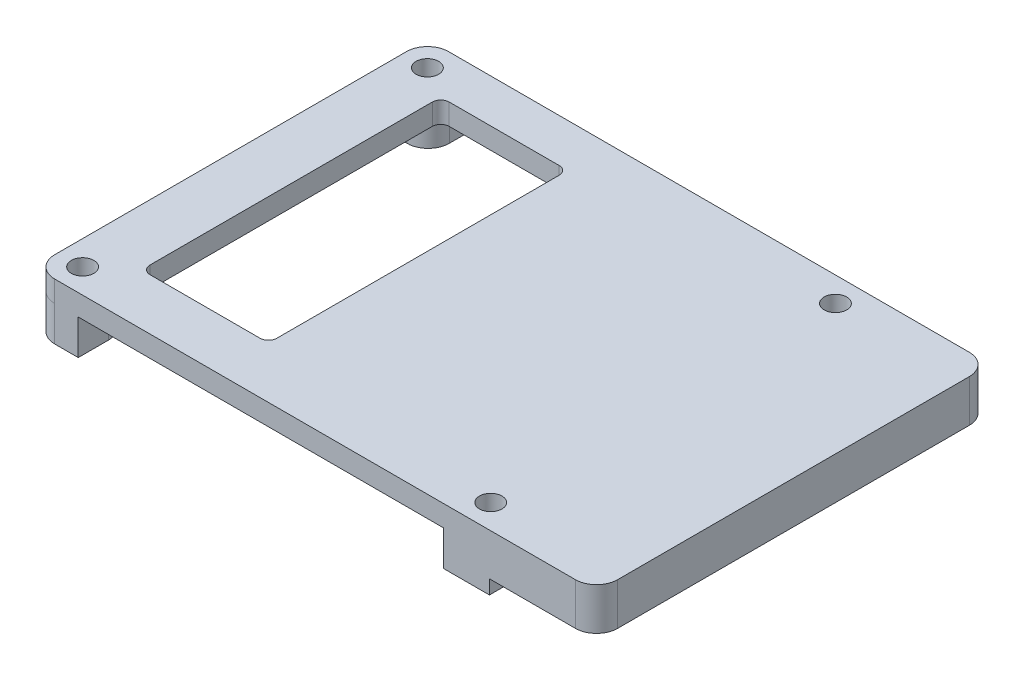
SolidWorks part; units mm, degrees
material "7075-T6 (SN)"
ref_plane "前视基准面" through (0, 0, 0) normal (0, 0, 1) x (1, 0, 0)
ref_plane "上视基准面" through (0, 0, 0) normal (0, 1, 0) x (1, 0, 0)
ref_plane "右视基准面" through (0, 0, 0) normal (1, 0, 0) x (0, 0, -1)
other "Configuration Table"
sketch "草图1" plane through (0, 0, 0) normal (0, 1, 0) x (1, 0, 0)
  line L0 (-70.9525, 18.3001) -> (-70.9986, 18.1669) construction
  line L5 (-80.009, 21.4027) -> (-0.009, 21.4027) construction
  line L6 (-0.009, 21.39) -> (-0.009, -28.5917)
  line L7 (-53.9406, -24.2884) -> (-53.9406, -23.4455) construction
  line L12 (-80.009, 21.4027) -> (-80.009, -28.6044)
  line L13 (-77.0217, -31.5917) -> (12.7873, -31.5917)
  line L14 (15.7746, -28.6044) -> (15.7746, 21.4027)
  line L15 (12.7873, 24.39) -> (-77.0217, 24.39)
  line L16 (-80.009, 21.4027) -> (-80.009, -28.6044)
  line L17 (-77.0217, -31.5917) -> (-3.009, -31.5917)
  line L19 (-3.009, 24.39) -> (-77.0217, 24.39)
  line L20 (-57.0741, 18.2303) -> (-57.0142, 16.884) construction
  line L21 (-57.0142, 16.884) -> (-53.9406, 15.8369) construction
  line L24 (-71.9124, -31.5917) -> (-71.9124, -38.4632) construction
  line L26 (-55.8106, -26.0508) -> (-55.3191, -21.9005) construction
  line L27 (-55.3191, -21.9005) -> (-52.2337, -21.9005) construction
  line L28 (-57.0741, 18.2303) -> (-53.9406, 18.2303) construction
  line L30 (-53.9406, 15.8369) -> (-53.9406, 18.2303) construction
  line L31 (-71.9686, 17.09) -> (-71.9659, 15.0188) construction
  line L32 (-54.4169, -24.2884) -> (-53.9406, -24.2884) construction
  line L33 (-70.9986, 18.1669) -> (-70.8339, 18.1567) construction
  line L34 (-70.8339, 18.1567) -> (-70.8158, 18.2696) construction
  line L35 (-70.8158, 18.2696) -> (-70.9525, 18.3001) construction
  line L36 (-70.8221, 18.2303) -> (-69.2002, 18.2303) construction
  line L38 (-70.7701, 18.2303) -> (-55.1406, 18.2303)
  line L39 (-71.9701, 17.0303) -> (-71.9701, -23.0884)
  line L40 (-70.7701, -24.2884) -> (-55.1406, -24.2884)
  line L41 (-53.9406, 17.0303) -> (-53.9406, -23.0884)
  arc A0 (-70.7701, 18.2303) -> (-71.9701, 17.0303) centre (-70.7701, 17.0303) ccw
  arc A1 (-53.9406, 17.0303) -> (-55.1406, 18.2303) centre (-55.1406, 17.0303) ccw
  arc A2 (-53.9406, -23.0884) -> (-55.1406, -24.2884) centre (-55.1406, -23.0884) cw
  arc A3 (-70.7701, -24.2884) -> (-71.9701, -23.0884) centre (-70.7701, -23.0884) cw
  circle A4 centre (-76.5285, 20.8867) radius 1.6
  circle A5 centre (-18.5286, 20.8866) radius 1.6
  circle A6 centre (-18.5283, -28.1137) radius 1.6
  circle A7 centre (-76.5283, -28.1135) radius 1.6
  arc A8 (-80.009, -28.6044) -> (-77.0217, -31.5917) centre (-77.0217, -28.6044) ccw
  arc A9 (12.7873, -31.5917) -> (15.7746, -28.6044) centre (12.7873, -28.6044) ccw
  arc A10 (15.7746, 21.4027) -> (12.7873, 24.39) centre (12.7873, 21.4027) ccw
  arc A11 (-77.0217, 24.39) -> (-80.009, 21.4027) centre (-77.0217, 21.4027) ccw
  arc A12 (-80.009, -28.6044) -> (-77.0217, -31.5917) centre (-77.0217, -28.6044) ccw
  arc A15 (-77.0217, 24.39) -> (-80.009, 21.4027) centre (-77.0217, 21.4027) ccw
  arc A19 (-0.009, 21.39) -> (-3.009, 24.39) centre (-3.009, 21.39) ccw
  arc A20 (-0.009, -28.5917) -> (-3.009, -31.5917) centre (-3.009, -28.5917) cw
  dimension "D2" = 3.2
  dimension "D3" = 3.2
  dimension "D4" = 3.2
  dimension "D5" = 3.2
  dimension "D6" = 3
  dimension "D7" = 1.2
  dimension "D8" = 1.2
  dimension "D9" = 1.2
  dimension "D10" = 1.2
  dimension "D11" = 3
  dimension "D1" = 0
extrude "凸台-拉伸1" add sketch "草图1" along normal blind 3
sketch "草图3" plane through (0, 0, 0) normal (0, -1, 0) x (1, 0, 0)
  line L0 (-77.0217, 31.5917) -> (-3.009, 31.5917) construction
  line L1 (-15.2271, 31.5917) -> (-3.009, 31.5917)
  line L2 (-15.2271, 31.5917) -> (-15.2271, -24.39)
  line L3 (-15.2271, -24.39) -> (-3.009, -24.39)
  line L7 (-36.8658, -15.5141) -> (-24.8441, -15.5141)
  line L8 (-36.8658, -15.5141) -> (-36.8658, 23.3522)
  line L9 (-36.8658, 23.3522) -> (-24.8441, 23.3522)
  line L10 (-24.8441, -15.5141) -> (-24.8441, 23.3522)
  line L11 (-0.009, 28.5917) -> (-0.009, -21.39)
  arc A0 (-0.009, -21.39) -> (-3.009, -24.39) centre (-3.009, -21.39) cw
  arc A1 (-3.009, 31.5917) -> (-0.009, 28.5917) centre (-3.009, 28.5917) cw
  dimension "D1" = 3
  dimension "D2" = 3
extrude "凸台-拉伸3" add sketch "草图3" along normal blind 3
sketch "草图4" plane through (0, 0, 0) normal (0, -1, 0) x (1, 0, 0)
  line L0 (-80.009, 24.3217) -> (-76.6695, 24.3217)
  line L1 (-80.009, -21.4027) -> (-80.009, 28.6044) construction
  line L2 (-15.2271, 31.5917) -> (-15.2271, -24.39) construction
  line L3 (-15.2271, 24.3217) -> (-15.2271, 31.5917)
  line L4 (-15.2271, 31.5917) -> (-21.7271, 31.5917)
  line L5 (-77.0217, 31.5917) -> (-15.2271, 31.5917) construction
  line L6 (-21.7271, 31.5917) -> (-21.7271, 27.3217)
  line L7 (-21.7271, -21.1423) -> (-21.7271, -24.39)
  line L8 (-73.6695, 27.3217) -> (-73.6695, 31.5917)
  line L9 (-18.7271, 24.3217) -> (-15.2271, 24.3217)
  line L10 (-80.009, 24.3217) -> (-80.009, 28.5917)
  line L11 (-77.009, 31.5917) -> (-73.6695, 31.5917)
  line L16 (-80.009, -18.1423) -> (-76.6695, -18.1423)
  line L17 (-73.6695, -21.1423) -> (-73.6695, -24.3882)
  line L18 (-73.6695, -24.3882) -> (-77.009, -24.3882)
  line L19 (-80.009, -21.3882) -> (-80.009, -18.1423)
  line L20 (-18.7271, -18.1423) -> (-15.2271, -18.1423) construction
  line L21 (-18.7271, -18.1423) -> (-15.2271, -18.1423)
  line L22 (-15.2271, -18.1423) -> (-15.2271, -24.39)
  line L23 (-15.2271, -24.39) -> (-21.7271, -24.39)
  line L24 (-15.2271, -24.39) -> (-77.0217, -24.39) construction
  line L25 (-73.6695, -19.7285) -> (-73.6695, -28.5591) construction
  line L34 (-76.6695, -18.1423) -> (-92.8145, -18.1423) construction
  circle A0 centre (-76.5283, 28.1135) radius 1.6
  circle A1 centre (-18.5283, 28.1137) radius 1.6
  circle A2 centre (-18.5286, -20.8866) radius 1.6
  circle A3 centre (-76.5285, -20.8867) radius 1.6
  arc A4 (-80.009, 28.5917) -> (-77.009, 31.5917) centre (-77.009, 28.5917) cw
  arc A6 (-77.009, -24.3882) -> (-80.009, -21.3882) centre (-77.009, -21.3882) cw
  arc A10 (-18.7271, 24.3217) -> (-21.7271, 27.3217) centre (-18.7271, 27.3217) cw
  arc A11 (-18.7271, -18.1423) -> (-21.7271, -21.1423) centre (-18.7271, -21.1423) ccw
  arc A12 (-73.6695, -21.1423) -> (-76.6695, -18.1423) centre (-76.6695, -21.1423) ccw
  arc A13 (-73.6695, 27.3217) -> (-76.6695, 24.3217) centre (-76.6695, 27.3217) cw
  point P45 (-73.6695, -18.1423)
  point P57 (-21.7271, 24.3217)
  dimension "D1" = 3
  dimension "D2" = 3
  dimension "D3" = 3
  dimension "D4" = 3
  dimension "D5" = 3
  dimension "D6" = 3
  dimension "D7" = 6.5
  dimension "D8" = 6.5
extrude "凸台-拉伸4" add sketch "草图4" along normal blind 5
